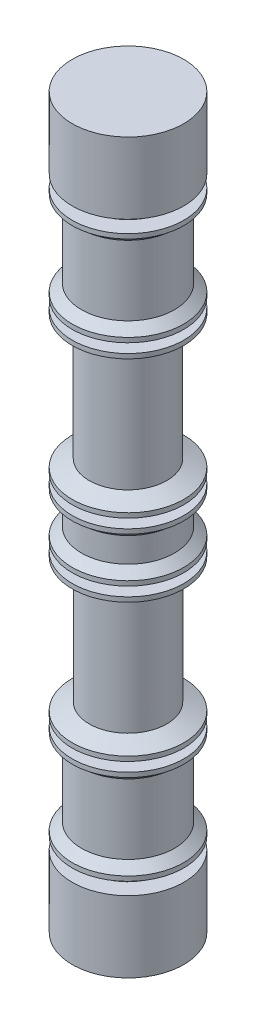
SolidWorks part; units mm, degrees
material "6061-T6 (SS)"
ref_plane "Front Plane" through (0, 0, 0) normal (0, 0, 1) x (1, 0, 0)
ref_plane "Top Plane" through (0, 0, 0) normal (0, 1, 0) x (1, 0, 0)
ref_plane "Right Plane" through (0, 0, 0) normal (1, 0, 0) x (0, 0, -1)
sketch "MidBodyS" plane through (0, 0, 0) normal (0, 1, 0) x (1, 0, 0)
  circle A0 centre (0, 0) radius 3
  dimension "Dia" = 6
extrude "MidBody" add sketch "MidBodyS" along normal blind 0.8
sketch "MidORingBaseS" plane through (0, 0, 0) normal (0, 0, 1) x (1, 0, 0)
  line L0 (3, 0.8) -> (3.6, 1.3)
  line L1 (3.6, 1.3) -> (3.6, 1.6)
  line L2 (3.6, 1.6) -> (0, 1.6)
  line L3 (0, 1.6) -> (0, 0.8) construction
  line L4 (3, 0.8) -> (-3, 0.8) construction
  line L5 (0, 0.8) -> (3, 0.8)
  line L6 (0, 1.6) -> (0, 0.8) construction
  line L7 (0, 1.6) -> (0, 0.8)
  dimension "EdgeHeight" = 0.3
  dimension "Height" = 0.8
  dimension "DiaControl" = 0.6
  dimension "RefDia" = 7.2
revolve "MidORingBase" add sketch "MidORingBaseS" angle 360 about L7
sketch "MidORingBodyS" plane through (0, 1.6, 0) normal (0, 1, 0) x (1, 0, 0)
  circle A0 centre (0, 0) radius 2.5
  circle A2 centre (0, 0) radius 3.6 construction
  dimension "RefDia" = 5
  dimension "DiaContro" = 1.1
extrude "MidORingBody" add sketch "MidORingBodyS" along normal blind 0.6
sketch "MidORingTopBaseS" plane through (0, 0, 0) normal (0, 0, 1) x (1, 0, 0)
  line L0 (0, 2.2) -> (3.6, 2.2)
  line L1 (2.5, 2.2) -> (-2.5, 2.2) construction
  line L2 (3.6, 2.2) -> (3.6, 2.5)
  line L3 (3.6, 2.5) -> (2.5, 3)
  line L4 (2.5, 3) -> (0, 3)
  line L5 (0, 2.2) -> (0, 3) construction
  line L6 (3.6, 1.3) -> (3.6, 1.6) construction
  line L7 (0, 2.2) -> (0, 3)
  dimension "Height" = 0.8
  dimension "DiaControl" = 1.1
  dimension "RefDia" = 5
revolve "MidORingTopBase" add sketch "MidORingTopBaseS" angle 360 about L5
sketch "ExtendedMidBodyS" plane through (0, 3, 0) normal (0, 1, 0) x (1, 0, 0)
  circle A1 centre (0, 0) radius 2.5
  circle A2 centre (0, 0) radius 2.5
  dimension "D1" = 0
extrude "ExtendedMidBody" add sketch "ExtendedMidBodyS" along normal blind 7.6
sketch "2ndORingBaseS" plane through (0, 0, 0) normal (0, 0, 1) x (1, 0, 0)
  line L0 (0, 10.6) -> (0, 11.4) construction
  line L1 (2.5, 10.6) -> (-2.5, 10.6) construction
  line L2 (0, 11.4) -> (3.6, 11.4)
  line L3 (3.6, 11.4) -> (3.6, 11.1)
  line L4 (3.6, 11.1) -> (2.5, 10.6)
  line L5 (2.5, 10.6) -> (0, 10.6)
  line L6 (3.6, 1.3) -> (3.6, 1.6) construction
  line L7 (2.5, 3) -> (2.5, 10.6) construction
  line L8 (0, 10.6) -> (0, 11.4)
  dimension "Height" = 0.8
revolve "2ndORingBase" add sketch "2ndORingBaseS" angle 360 about L0
sketch "2ndORingBodyS" plane through (0, 11.4, 0) normal (0, 1, 0) x (1, 0, 0)
  circle A0 centre (0, 0) radius 2.5
  circle A1 centre (0, 0) radius 3.6 construction
  dimension "DiaControl" = 1.1
extrude "2ndORingBody" add sketch "2ndORingBodyS" along normal blind 0.6
sketch "2ndORingBaseTopS" plane through (0, 0, 0) normal (0, 0, 1) x (1, 0, 0)
  line L0 (0, 12) -> (3.6, 12)
  line L1 (2.5, 12) -> (-2.5, 12) construction
  line L2 (3.6, 12) -> (3.6, 12.3)
  line L3 (3.6, 12.3) -> (3, 12.8)
  line L4 (3, 12.8) -> (0, 12.8)
  line L5 (0, 12.8) -> (0, 12)
  line L6 (3.6, 11.1) -> (3.6, 11.4) construction
  line L7 (0, 10.6) -> (0, 11.4) construction
  line L8 (3.6, 11.4) -> (3.6, 11.1) construction
  dimension "D1" = 3
revolve "2ndORingBaseTop" add sketch "2ndORingBaseTopS" angle 360 about L5
sketch "2ndExtendedBodyS" plane through (0, 12.8, 0) normal (0, 1, 0) x (1, 0, 0)
  circle A0 centre (0, 0) radius 3
  circle A2 centre (0, 0) radius 3 construction
extrude "2ndExtendedBody" add sketch "2ndExtendedBodyS" along normal blind 4.5
sketch "3rdORingBaseS" plane through (0, 0, 0) normal (0, 0, 1) x (1, 0, 0)
  line L0 (0, 17.3) -> (3, 17.3)
  line L1 (3, 17.3) -> (3.6, 17.8)
  line L2 (3.6, 17.8) -> (3.6, 18.1)
  line L3 (3.6, 18.1) -> (0, 18.1)
  line L4 (0, 18.1) -> (0, 17.3)
  line L5 (3.6, 1.3) -> (3.6, 1.6) construction
  line L6 (3, 17.3) -> (-3, 17.3) construction
  line L7 (0, 1.6) -> (0, 0.8) construction
revolve "3rdORingBase" add sketch "3rdORingBaseS" angle 360 about L4
sketch "3rdORingBodyS" plane through (0, 18.1, 0) normal (0, 1, 0) x (1, 0, 0)
  circle A0 centre (0, 0) radius 2.5
  circle A1 centre (0, 0) radius 2.5 construction
extrude "3rdORingBody" add sketch "3rdORingBodyS" along normal blind 0.8
sketch "EndBodyS" plane through (0, 18.9, 0) normal (0, 1, 0) x (1, 0, 0)
  circle A0 centre (0, 0) radius 3.6
  circle A2 centre (0, 0) radius 3.6 construction
extrude "EndBody" add sketch "EndBodyS" along normal blind 4.6
mirror "HalfBodyVM" about plane through (0, 0, 0) normal (0, 1, 0) of "MidBody", "MidORingBase", "MidORingBody", "MidORingTopBase", "ExtendedMidBody", "2ndORingBase", "2ndORingBody", "2ndORingBaseTop", "2ndExtendedBody", "3rdORingBase", "3rdORingBody", "EndBody"
hole_wizard "Ø4.0 (4) Diameter Hole1" positions "Sketch9" profile "HoleProfile" hole size "Ø4.0" standard "ANSI Metric"
sketch "Sketch9" plane through (0, -23.5, 0) normal (0, -1, 0) x (-1, 0, 0)
  point P0 (0, 0)
sketch "HoleProfile" plane through (0, -23.5, 0) normal (1, 0, 0) x (0, 0, -1)
  line L0 (0, 0) -> (0, 10.6017)
  line L1 (0, 10.6017) -> (2, 9.4)
  line L2 (2, 9.4) -> (2, 0)
  line L5 (2, 0) -> (0, 0)
  line L10 (0, 10.6017) -> (-2, 9.4) construction
  line L11 (0, -6.35) -> (0, 107.95) construction
  dimension "Hole Dia." = 4
  dimension "Hole Depth" = 9.4
  dimension "Drill Angle" = 118
equation "\"DiaControl@2ndORingBodyS\" = \"DiaContro@MidORingBodyS\""
equation "\"Height@2ndORingBody\" = \"Height@MidORingBody\""
equation "\"Height@3rdORingBody\" = \"Height@MidORingBody\""
